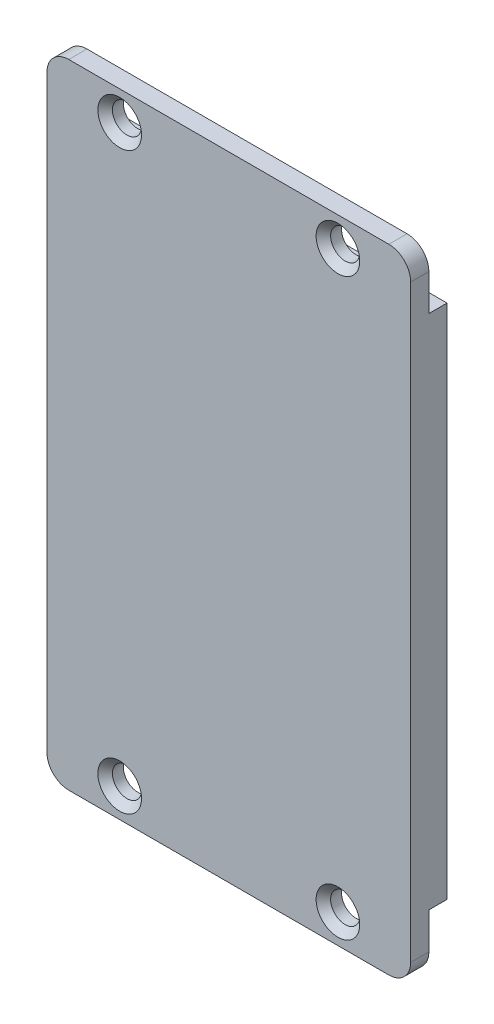
SolidWorks part; units mm, degrees
ref_plane "Plan de face" through (0, 0, 0) normal (0, 0, 1) x (1, 0, 0)
ref_plane "Plan de dessus" through (0, 0, 0) normal (0, 1, 0) x (1, 0, 0)
ref_plane "Plan de droite" through (0, 0, 0) normal (1, 0, 0) x (0, 0, -1)
sketch "Esquisse1" plane through (0, 0, 0) normal (0, 0, 1) x (1, 0, 0)
  line L1 (0, 0) -> (50, 0)
  line L2 (0, 0) -> (0, 71)
  line L3 (0, 71) -> (50, 71)
  line L4 (50, 0) -> (50, 71)
  dimension "D1" = 50
  dimension "D2" = 71
extrude "Boss.-Extru.1" add sketch "Esquisse1" along normal blind 2.5
sketch "Esquisse2" plane through (0, 0, 2.5) normal (0, 0, 1) x (1, 0, 0)
  line L0 (50, 71) -> (0, 71) construction
  line L1 (0, 79) -> (50, 79)
  line L2 (0, 79) -> (0, -8)
  line L3 (0, -8) -> (50, -8)
  line L4 (50, 79) -> (50, -8)
  line L5 (0, 0) -> (50, 0) construction
  dimension "D1" = 50
  dimension "D2" = 8
  dimension "D3" = 8
extrude "Boss.-Extru.2" add sketch "Esquisse2" along normal blind 2.5
fillet "Congé1" radius 3 4 edges at (50, 79, 3.75) (0, 79, 3.75) (0, -8, 3.75) (50, -8, 3.75)
sketch "Esquisse3" plane through (0, 0, 2.5) normal (0, 0, -1) x (-1, 0, 0)
  line L0 (-50, 71) -> (-50, 76) construction
  line L1 (0, 76) -> (0, 71) construction
  line L2 (-50, 71) -> (0, 71) construction
  line L3 (0, 0) -> (-50, 0) construction
  line L4 (-50, -5) -> (-50, 0) construction
  line L5 (0, 0) -> (0, -5) construction
  circle A0 centre (-40, 75) radius 2
  circle A1 centre (-10, 75) radius 2
  circle A2 centre (-10, -4) radius 2
  circle A3 centre (-40, -4) radius 2
  point P8 (-50, 73.5)
  dimension "D1" = 4
  dimension "D2" = 4
  dimension "D3" = 4
  dimension "D4" = 4
  dimension "D5" = 10
  dimension "D6" = 10
  dimension "D7" = 4
  dimension "D8" = 4
  dimension "D9" = 4
  dimension "D10" = 4
  dimension "D11" = 10
  dimension "D12" = 10
extrude "Enlèv. mat.-Extru.1" cut sketch "Esquisse3" against normal blind 2.5
chamfer "Chanfrein1" distance 1 angle 45 4 edges at (38, -4, 5) (8, -4, 5) (8, 75, 5) (38, 75, 5)
sketch "Esquisse5" plane through (0, 0, 0) normal (0, 0, -1) x (-1, 0, 0)
  text T0 "Club\r\nRobotique \r\nIsen" font "Soopafresh" height in points 18
extrude "Enlèv. mat.-Extru.2" cut sketch "Esquisse5" against normal blind 2
